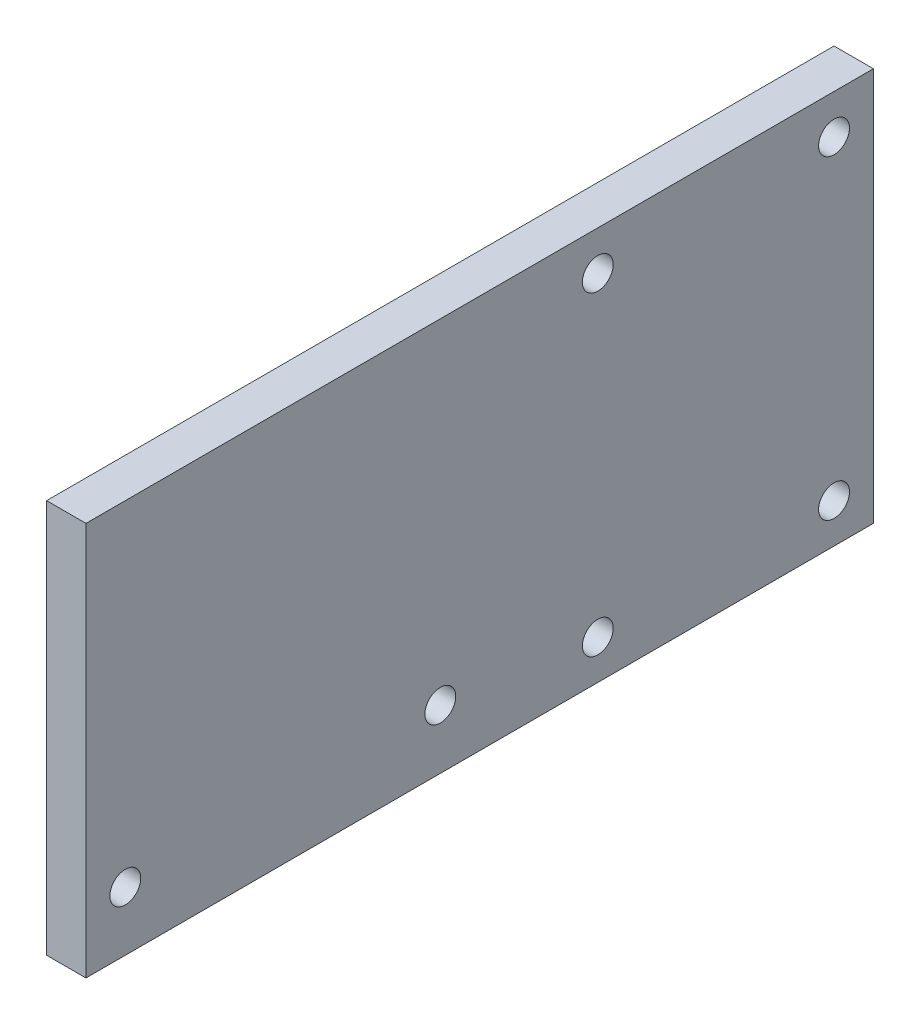
SolidWorks part; units mm, degrees
ref_plane "Front" through (0, 0, 0) normal (0, 0, 1) x (1, 0, 0)
ref_plane "Top" through (0, 0, 0) normal (0, 1, 0) x (1, 0, 0)
ref_plane "Right" through (0, 0, 0) normal (1, 0, 0) x (0, 0, -1)
sketch "Sketch1" plane through (0, 0, 0) normal (1, 0, 0) x (0, 0, -1)
  line L1 (-63.5, -31.75) -> (63.5, -31.75)
  line L2 (-63.5, -31.75) -> (-63.5, 31.75)
  line L3 (-63.5, 31.75) -> (63.5, 31.75)
  line L4 (63.5, -31.75) -> (63.5, 31.75)
  line L5 (-63.5, -31.75) -> (63.5, 31.75) construction
  line L6 (-63.5, 31.75) -> (63.5, -31.75) construction
  point P0 (0, 0)
  dimension "D1" = 127
  dimension "D2" = 63.5
extrude "Boss-Extrude1" add sketch "Sketch1" along normal blind 6.35
hole_wizard "#9 (0.196) Diameter Hole1" positions "Sketch3" profile "Sketch2" hole size "#9" standard "ANSI Inch"
sketch "Sketch3" plane through (0, 0, 0) normal (-1, 0, 0) x (0, 0, 1)
  line L0 (63.5, -31.75) -> (-63.5, -31.75) construction
  line L1 (63.5, 31.75) -> (63.5, -31.75) construction
  point P0 (57.15, -22.225)
  point P2 (6.35, -22.225)
  dimension "D1" = 9.525
  dimension "D2" = 0
  dimension "D3" = 50.8
  dimension "D4" = 6.35
sketch "Sketch2" plane through (0, -22.225, 57.15) normal (0, 1, 0) x (0, 0, 1)
  line L0 (0, 0) -> (0, 71.5997)
  line L1 (0, 71.5997) -> (2.4892, 70.104)
  line L2 (2.4892, 70.104) -> (2.4892, 0)
  line L5 (2.4892, 0) -> (0, 0)
  line L10 (0, 71.5997) -> (-2.4892, 70.104) construction
  line L11 (0, -6.35) -> (0, 107.95) construction
  dimension "Hole Dia." = 4.9784
  dimension "Hole Depth" = 70.104
  dimension "Drill Angle" = 118
hole_wizard "#9 (0.196) Diameter Hole2" positions "Sketch5" profile "Sketch4" hole size "#9" standard "ANSI Inch"
sketch "Sketch5" plane through (0, 0, 0) normal (-1, 0, 0) x (0, 0, 1)
  line L0 (63.5, -31.75) -> (-63.5, -31.75) construction
  line L1 (-63.5, -31.75) -> (-63.5, 31.75) construction
  point P0 (-57.15, -25.4)
  point P2 (-19.05, -25.4)
  point P4 (-19.05, 25.4)
  point P6 (-57.15, 25.4)
  dimension "D1" = 6.35
  dimension "D2" = 6.35
  dimension "D3" = 0
  dimension "D4" = 50.8
  dimension "D5" = 38.1
  dimension "D6" = 50.8
  dimension "D7" = 38.1
  dimension "D8" = 0
sketch "Sketch4" plane through (0, -25.4, -57.15) normal (0, 1, 0) x (0, 0, 1)
  line L0 (0, 0) -> (0, 71.5997)
  line L1 (0, 71.5997) -> (2.4892, 70.104)
  line L2 (2.4892, 70.104) -> (2.4892, 0)
  line L5 (2.4892, 0) -> (0, 0)
  line L10 (0, 71.5997) -> (-2.4892, 70.104) construction
  line L11 (0, -6.35) -> (0, 107.95) construction
  dimension "Hole Dia." = 4.9784
  dimension "Hole Depth" = 70.104
  dimension "Drill Angle" = 118
